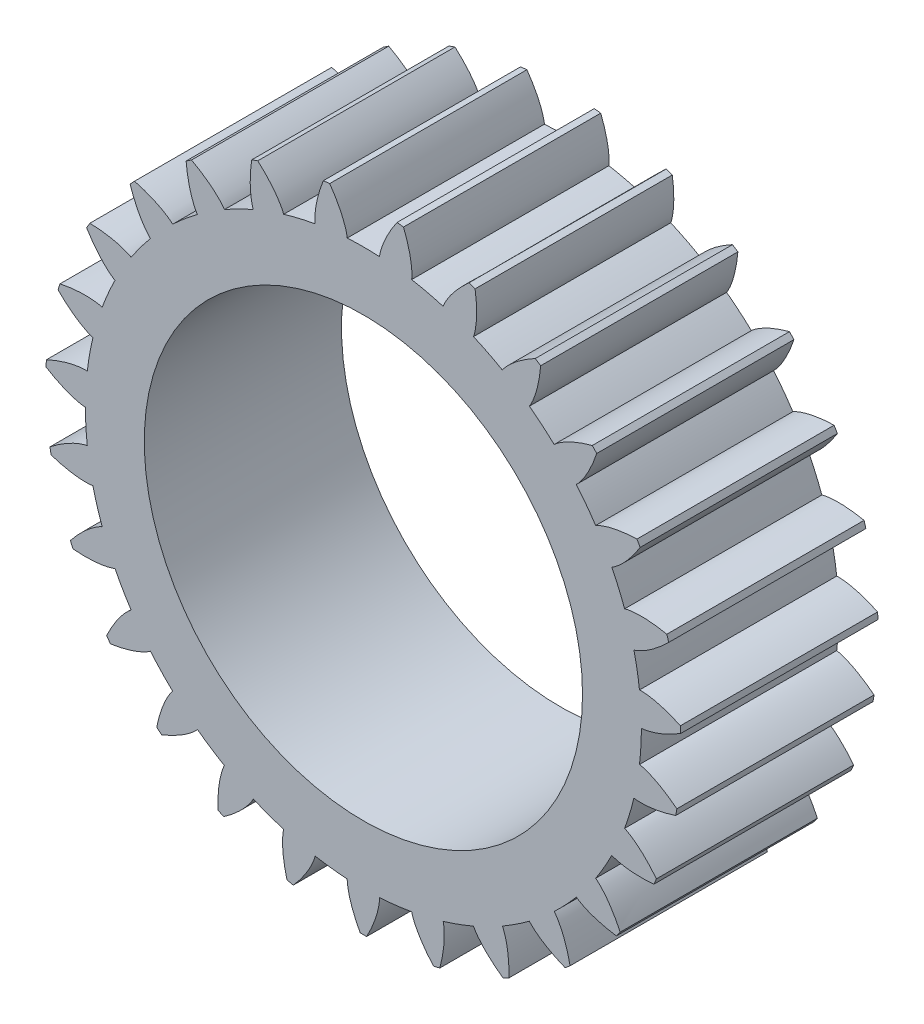
SolidWorks part; units mm, degrees
ref_plane "Front Plane" through (0, 0, 0) normal (0, 0, 1) x (1, 0, 0)
ref_plane "Top Plane" through (0, 0, 0) normal (0, 1, 0) x (1, 0, 0)
ref_plane "Right Plane" through (0, 0, 0) normal (1, 0, 0) x (0, 0, -1)
sketch "Sketch1" plane through (0, 0, 0) normal (0, 0, 1) x (1, 0, 0)
  line L0 (0, 0) -> (32.1677, -1.8736) construction
  line L1 (0, 0) -> (32.1677, 1.8736) construction
  line L2 (0, 0) -> (32.1677, -1.8736) construction
  line L3 (0, 0) -> (32.2222, 0) construction
  line L4 (0, 0) -> (31.7327, 5.5953) construction
  line L5 (22.1846, 1.2921) -> (32.1677, 1.8736)
  line L6 (22.1846, -1.2921) -> (28.1431, -1.6391)
  line L7 (28.1908, 0) -> (48.983, 0)
  circle A0 centre (0, 0) radius 30 construction
  circle A1 centre (0, 0) radius 27.2222 construction
  circle A2 centre (0, 0) radius 28.1908 construction
  circle A3 centre (0, 0) radius 32.2222 construction
  arc A4 (22.1846, 1.2921) -> (22.1846, -1.2921) centre (0, 0) cw
  arc A5 (28.1431, -1.6391) -> (28.1894, 0.2756) centre (0, 0) ccw
  arc A6 (32.1677, 1.8736) -> (32.1851, 1.5459) centre (0, 0) cw
  spline S0 degree 4 poles (28.1908, 0) (28.228, 0.0011) (28.3023, 0.0054) (28.5101, 0.0281) (28.9022, 0.0992) (29.4929, 0.2558) (30.2824, 0.5425) (31.2625, 0.9958) (32.3595, 1.6261) (33.5016, 2.4185) (34.6589, 3.37) (35.7436, 4.4033) (36.7568, 5.5064) (37.7467, 6.7274) (38.8771, 8.3118) (40.0789, 10.2986) (41.271, 12.7185) (42.3445, 15.5172) (43.1763, 18.3964) (43.776, 21.3325) (44.1527, 24.305) (44.3156, 27.2967) (44.2788, 29.9178) (44.1374, 31.9721) (43.9793, 33.4603) (43.8371, 34.5746) (43.6724, 35.6837) (43.4781, 36.7925) (43.2581, 37.889) (43.0537, 38.8085) (42.8844, 39.5249) (42.7108, 40.2082) (42.5637, 40.7635) (42.3873, 41.3944) (42.2694, 41.8019) (42.0732, 42.4584) (41.9123, 42.9664) (41.7131, 43.5823) (41.5269, 44.1284) (41.3218, 44.7155) (41.1191, 45.2701) (40.9566, 45.7041) (40.8499, 45.9799) (40.7944, 46.123) knots 0 0 0 0 0 0.002802 0.005604 0.015718 0.02996 0.048734 0.068727 0.096889 0.125051 0.153212 0.181374 0.209535 0.237696 0.271429 0.327752 0.384075 0.440398 0.496721 0.553044 0.609367 0.66569 0.722013 0.750174 0.764255 0.778336 0.806497 0.834659 0.84874 0.86282 0.876901 0.890982 0.900036 0.909091 0.920455 0.931818 0.943182 0.954545 0.965909 0.977273 0.988636 1 1 1 1 1 construction
  spline S1 degree 4 poles (28.1908, 0) (28.228, 0.0011) (28.3023, 0.0054) (28.5101, 0.0281) (28.9022, 0.0992) (29.4929, 0.2558) (30.2824, 0.5425) (31.2625, 0.9958) (32.3595, 1.6261) (33.5016, 2.4185) (34.6589, 3.37) (35.7436, 4.4033) (36.7568, 5.5064) (37.7467, 6.7274) (38.8771, 8.3118) (40.0789, 10.2986) (41.271, 12.7185) (42.3445, 15.5172) (43.1763, 18.3964) (43.776, 21.3325) (44.1527, 24.305) (44.3156, 27.2967) (44.2788, 29.9178) (44.1374, 31.9721) (43.9793, 33.4603) (43.8371, 34.5746) (43.6724, 35.6837) (43.4781, 36.7925) (43.2581, 37.889) (43.0537, 38.8085) (42.8844, 39.5249) (42.7108, 40.2082) (42.5637, 40.7635) (42.4333, 41.2298) (42.3729, 41.442) (42.3426, 41.5471) knots 0 0 0 0 0 0.002802 0.005604 0.015718 0.02996 0.048734 0.068727 0.096889 0.125051 0.153212 0.181374 0.209535 0.237696 0.271429 0.327752 0.384075 0.440398 0.496721 0.553044 0.609367 0.66569 0.722013 0.750174 0.764255 0.778336 0.806497 0.834659 0.84874 0.86282 0.876901 0.890982 0.900036 0.909091 0.909091 0.909091 0.909091 0.909091
  point P10 (27.1762, 1.5828)
  point P21 (27.2222, 0)
  dimension "pitchRadius" = 30
  dimension "addendumRadius" = 32.2222
  dimension "dedendumRadius" = 27.2222
  dimension "baseRadius" = 28.1908
  dimension "D1" = 6.667
  dimension "D2" = 3.333
  dimension "toothArc" = 13.333
  dimension "D3" = 5
extrude "Boss-Extrude1" add sketch "Sketch1" along normal blind 20
mirror "Mirror1" about plane through (0, 0, 20) normal (-0.0581, 0.9983, 0) of "Boss-Extrude1"
pattern_circular "CirPattern1" count 27 over 360 about axis through (0, 0, 20) along (0, 0, -1) of "Boss-Extrude1", "Mirror1"
equation "\"D1@Sketch1\"=\"toothArc@Sketch1\"/2"
equation "\"D2@Sketch1\"=\"toothArc@Sketch1\"/4"
equation "\"pitchRadius\" = 3"
equation "\"nTeeth\"= 27"
equation "\"pressureAngle\"= 20"
equation "\"baseRadius\"= \"pitchRadius\" * cos ( \"pressureAngle\" )"
equation "\"diametralPitch\"= \"nTeeth\" / ( 2 * \"pitchRadius\" )'note units: cm^-1"
equation "\"dedendum\"= 1.25 / \"diametralPitch\"'for full depth, 20 deg pressure angle"
equation "\"addendum\"= 1 / \"diametralPitch\""
equation "\"pitchRadius@Sketch1\"= \"pitchRadius\""
equation "\"addendumRadius@Sketch1\"= \"pitchRadius\" + \"addendum\""
equation "\"dedendumRadius@Sketch1\"= \"pitchRadius\" - \"dedendum\""
equation "\"baseRadius@Sketch1\"= \"baseRadius\""
equation "\"toothArc@Sketch1\"=360/\"nTeeth\""
equation "\"D1@CirPattern1\"=\"nTeeth\""
